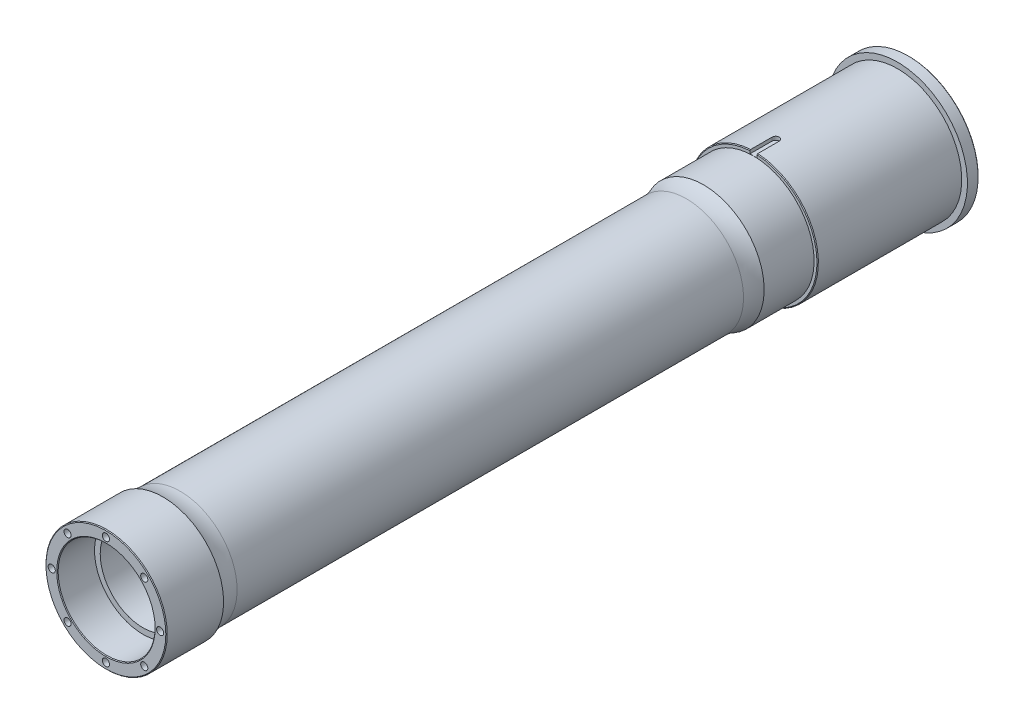
SolidWorks part; units mm, degrees
ref_plane "前视基准面" through (0, 0, 0) normal (0, 0, 1) x (1, 0, 0)
ref_plane "上视基准面" through (0, 0, 0) normal (0, 1, 0) x (1, 0, 0)
ref_plane "右视基准面" through (0, 0, 0) normal (1, 0, 0) x (0, 0, -1)
other "Configuration Table"
sketch "草图1" plane through (0, 0, 0) normal (1, 0, 0) x (0, 0, -1)
  line L0 (0, 0) -> (0, 42.5)
  line L1 (0, 42.5) -> (40, 42.5)
  line L2 (51.9896, 40) -> (407.0104, 40)
  line L3 (419, 42.5) -> (454, 42.5)
  line L4 (454, 42.5) -> (454, 45)
  line L5 (454, 45) -> (555, 45)
  line L6 (555, 45) -> (555, 49)
  line L7 (555, 49) -> (563, 49)
  line L8 (563, 49) -> (563, 0)
  line L9 (563, 0) -> (0, 0)
  line L10 (0, 0) -> (-72.3114, 0) construction
  arc A0 (40, 42.5) -> (51.9896, 40) centre (51.9896, 70) ccw
  arc A1 (407.0104, 40) -> (419, 42.5) centre (407.0104, 70) ccw
  point P10 (0, 0)
  dimension "D1" = 30
  dimension "D2" = 85
  dimension "D3" = 80
  dimension "D4" = 90
  dimension "D5" = 98
  dimension "D6" = 40
  dimension "D7" = 35
  dimension "D8" = 101
  dimension "D9" = 8
  dimension "D10" = 379
revolve "旋转1" add sketch "草图1" angle 360 about L10
sketch "草图2" plane through (0, 0, 0) normal (1, 0, 0) x (0, 0, -1)
  line L0 (0, 0) -> (-53.5447, 0) construction
  line L1 (0, 0) -> (0, 34)
  line L2 (0, 42.5) -> (0, -42.5) construction
  line L3 (0, 34) -> (26, 34)
  line L4 (26, 34) -> (26, 30)
  line L5 (26, 30) -> (537, 30)
  line L6 (537, 30) -> (537, 34)
  line L7 (537, 34) -> (563, 34)
  line L8 (563, -49) -> (563, 49) construction
  line L9 (563, 34) -> (563, 0)
  line L10 (563, 0) -> (0, 0)
  dimension "D1" = 68
  dimension "D2" = 60
  dimension "D3" = 68
  dimension "D4" = 26
  dimension "D5" = 26
revolve "切除-旋转1" cut sketch "草图2" angle 360 about L0
sketch "草图3" plane through (0, 0, 0) normal (0, 0, 1) x (1, 0, 0)
  circle A0 centre (0, 0) radius 38 construction
  circle A1 centre (0, 38) radius 2.5
  circle A2 centre (26.8701, 26.8701) radius 2.5
  circle A3 centre (38, 0) radius 2.5
  circle A4 centre (26.8701, -26.8701) radius 2.5
  circle A5 centre (0, -38) radius 2.5
  circle A6 centre (-26.8701, -26.8701) radius 2.5
  circle A7 centre (-38, 0) radius 2.5
  circle A8 centre (-26.8701, 26.8701) radius 2.5
  point P5 (0, 0)
  point P6 (38, 0)
  point P22 (0, 0)
  dimension "D1" = 76
  dimension "D2" = 5
  dimension "D3" = 8
extrude "切除-拉伸1" cut sketch "草图3" against normal blind 15
sketch "草图4" plane through (0, 0, -563) normal (0, 0, -1) x (-1, 0, 0)
  circle A0 centre (0, 0) radius 38 construction
  circle A1 centre (0, 38) radius 2.5
  circle A2 centre (26.8701, 26.8701) radius 2.5
  circle A3 centre (38, 0) radius 2.5
  circle A4 centre (26.8701, -26.8701) radius 2.5
  circle A5 centre (0, -38) radius 2.5
  circle A6 centre (-26.8701, -26.8701) radius 2.5
  circle A7 centre (-38, 0) radius 2.5
  circle A8 centre (-26.8701, 26.8701) radius 2.5
  point P5 (0, 0)
  point P6 (38, 0)
  point P22 (0, 0)
  dimension "D1" = 76
  dimension "D2" = 5
  dimension "D3" = 8
extrude "切除-拉伸2" cut sketch "草图4" against normal blind 15
chamfer "倒角1" distance 0.5 angle 45 5 edges at (-45, 0, -454) (-34, 0, 0) (-42.5, 0, 0) (-34, 0, -563) (-49, 0, -563)
ref_plane "基准面1" through (0, 42.5, 0) normal (0, 1, 0) x (1, 0, 0)
sketch "草图5" plane through (0, 42.5, 0) normal (0, 1, 0) x (1, 0, 0)
  line L0 (-2.5, 454) -> (-2.5, 469.5)
  line L1 (0, 454.5) -> (0, 555) construction
  line L2 (45, 454.5) -> (-45, 454.5) construction
  line L3 (-45, 555) -> (45, 555) construction
  line L4 (2.5, 454) -> (2.5, 469.5)
  line L5 (-2.5, 454) -> (2.5, 454)
  line L6 (-42.5, 454) -> (42.5, 454) construction
  arc A0 (-2.5, 469.5) -> (2.5, 469.5) centre (0, 469.5) cw
  dimension "D2" = 2.5
  dimension "D1" = 15.5
extrude "切除-拉伸3" cut sketch "草图5" along normal blind 15
